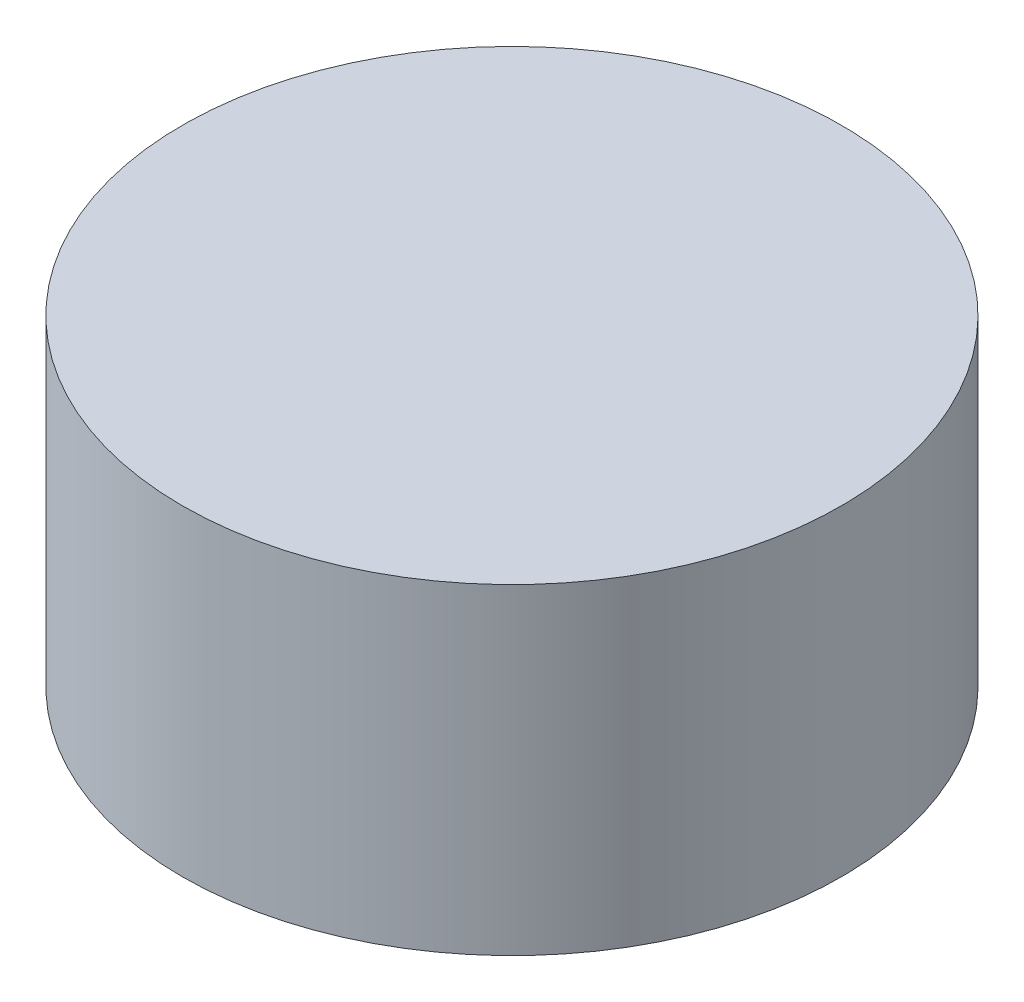
SolidWorks part; units mm, degrees
ref_plane "Front Plane" through (0, 0, 0) normal (0, 0, 1) x (1, 0, 0)
ref_plane "Top Plane" through (0, 0, 0) normal (0, 1, 0) x (1, 0, 0)
ref_plane "Right Plane" through (0, 0, 0) normal (1, 0, 0) x (0, 0, -1)
sketch "Sketch1" plane through (0, 0, 0) normal (0, 1, 0) x (1, 0, 0)
  circle A0 centre (0, 0) radius 2
  dimension "D1" = 4
extrude "Boss-Extrude1" add sketch "Sketch1" along normal blind 1.95
